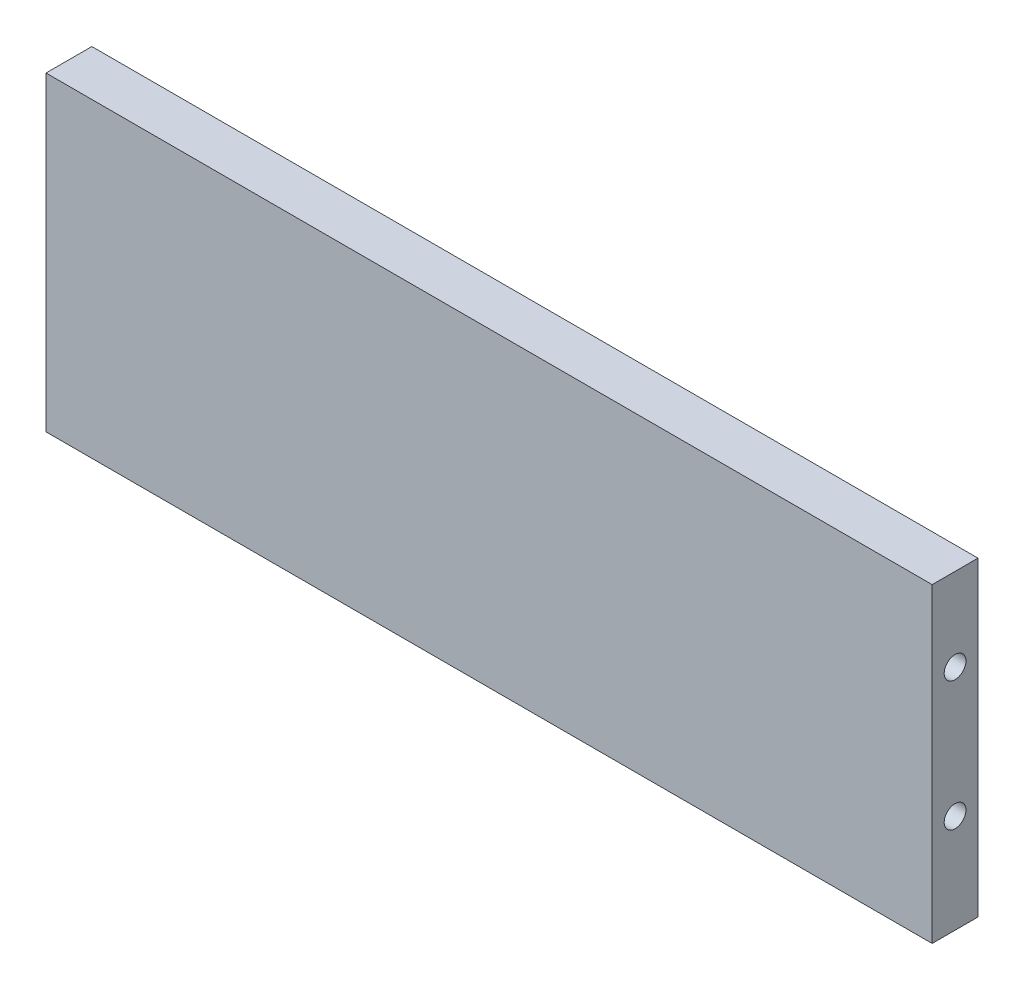
SolidWorks part; units mm, degrees
ref_plane "Front Plane" through (0, 0, 0) normal (0, 0, 1) x (1, 0, 0)
ref_plane "Top Plane" through (0, 0, 0) normal (0, 1, 0) x (1, 0, 0)
ref_plane "Right Plane" through (0, 0, 0) normal (1, 0, 0) x (0, 0, -1)
sketch "Sketch1" plane through (0, 0, 0) normal (0, 0, 1) x (1, 0, 0)
  line L1 (-46.0248, -16.1417) -> (46.0248, -16.1417)
  line L2 (-46.0248, -16.1417) -> (-46.0248, 16.1417)
  line L3 (-46.0248, 16.1417) -> (46.0248, 16.1417)
  line L4 (46.0248, -16.1417) -> (46.0248, 16.1417)
  line L5 (-46.0248, -16.1417) -> (46.0248, 16.1417) construction
  line L6 (-46.0248, 16.1417) -> (46.0248, -16.1417) construction
  point P0 (0, 0)
  dimension "D1" = 92.0496
  dimension "D2" = 32.2834
extrude "Boss-Extrude1" add sketch "Sketch1" along normal blind 4.7625
sketch "Sketch2" plane through (0, -16.1417, 0) normal (0, -1, 0) x (1, 0, 0)
  line L0 (46.0248, 4.7625) -> (46.0248, 0) construction
  line L1 (-46.0248, 4.7625) -> (-46.0248, 0) construction
  circle A0 centre (-20.6248, 2.3813) radius 1.1303
  circle A1 centre (20.6248, 2.3813) radius 1.1303
  point P8 (46.0248, 2.3813)
  dimension "D3" = 2.2606
  dimension "D1" = 25.4
  dimension "D2" = 25.4
extrude "Cut-Extrude1" cut sketch "Sketch2" against normal blind 19.05
sketch "Sketch3" plane through (-46.0248, 0, 0) normal (-1, 0, 0) x (0, 0, 1)
  circle A0 centre (2.3813, 7.5311) radius 1.1303
  circle A1 centre (2.3813, -5.8801) radius 1.1303
  circle A2 centre (2.3813, -5.8801) radius 1.524 construction
  circle A3 centre (2.3813, 7.5311) radius 1.524 construction
  dimension "D1" = 2.2606
extrude "Cut-Extrude2" cut sketch "Sketch3" against normal through all
